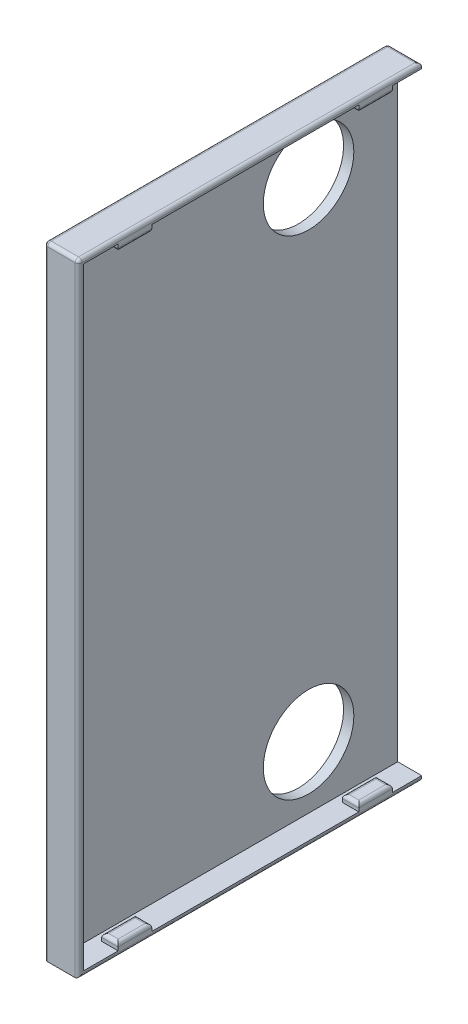
SolidWorks part; units mm, degrees
ref_plane "Plano frontal" through (0, 0, 0) normal (1, 0, 0) x (0, 1, 0)
ref_plane "Plano superior" through (0, 0, 0) normal (0, 0, 1) x (0, 1, 0)
ref_plane "Plano direito" through (0, 0, 0) normal (0, 1, 0) x (-1, 0, 0)
sketch "Esboço1" plane through (0, 0, 0) normal (1, 0, 0) x (0, 1, 0)
  line L1 (90.8, -51.55) -> (-90.8, -51.55)
  line L2 (90.8, -51.55) -> (90.8, 51.55)
  line L3 (90.8, 51.55) -> (-90.8, 51.55)
  line L4 (-90.8, -51.55) -> (-90.8, 51.55)
  line L5 (90.8, -51.55) -> (-90.8, 51.55) construction
  line L6 (90.8, 51.55) -> (-90.8, -51.55) construction
  point P0 (0, 0)
  dimension "D1" = 181.6
  dimension "D2" = 103.1
extrude "Ressalto-extrusão1" add sketch "Esboço1" along normal blind 10
sketch "Esboço2" plane through (10, 0, 0) normal (1, 0, 0) x (0, 1, 0)
  line L1 (89.3, -50.05) -> (-89.3, -50.05)
  line L2 (89.3, -50.05) -> (89.3, 50.05)
  line L3 (89.3, 50.05) -> (-89.3, 50.05)
  line L4 (-89.3, -50.05) -> (-89.3, 50.05)
  line L5 (89.3, -50.05) -> (-89.3, 50.05) construction
  line L6 (89.3, 50.05) -> (-89.3, -50.05) construction
  point P0 (0, 0)
  dimension "D1" = 178.6
  dimension "D2" = 100.1
extrude "Corte-extrusão1" cut sketch "Esboço2" against normal blind 7
sketch "Esboço4" plane through (0, -89.3, 0) normal (0, 1, 0) x (-1, 0, 0)
  line L0 (-10, 50.05) -> (-10, -50.05) construction
  line L1 (-10, 40) -> (-5.2, 40)
  line L2 (-10, 40) -> (-10, 30.2)
  line L3 (-10, 30.2) -> (-5.2, 30.2)
  line L4 (-5.2, 40) -> (-5.2, 30.2)
  line L5 (-3, 50.05) -> (-10, 50.05) construction
  dimension "D1" = 9.8
  dimension "D2" = 4.8
  dimension "D3" = 10.05
extrude "Ressalto-extrusão2" add sketch "Esboço4" along normal blind 2 contours L1 L4 L3 L2
mirror "Espelhar1" about plane through (0, 0, 0) normal (0, 0, 1) of "Ressalto-extrusão2"
mirror "Espelhar2" about plane through (0, 0, 0) normal (0, 1, 0) of "Espelhar1", "Ressalto-extrusão2"
sketch "Esboço5" plane through (0, 0, -51.55) normal (0, 0, -1) x (1, 0, 0)
  line L1 (0, 90.8) -> (10, 90.8)
  line L2 (0, 90.8) -> (0, -90.8)
  line L3 (0, -90.8) -> (10, -90.8)
  line L4 (10, 90.8) -> (10, -90.8)
extrude "Corte-extrusão2" cut sketch "Esboço5" against normal blind 3
fillet "Filete3" radius 1 10 edges at (5, -90.8, -48.55) (5, 90.8, -48.55) (10, 90.8, 1.5) (10, -90.8, 1.5) (10, 0, 51.55) (0, -90.8, 1.5) (0, 0, -48.55) (0, 90.8, 1.5) (0, 0, 51.55) (5, 90.8, 51.55)
fillet "Filete6" radius 1 4 edges at (7.6, -87.3, 40) (5.2, -87.3, 35.1) (7.6, -87.3, 30.2) (10, -87.3, 35.1)
fillet "Filete7" radius 1 4 edges at (7.6, -87.3, -30.2) (5.2, -87.3, -35.1) (7.6, -87.3, -40) (10, -87.3, -35.1)
fillet "Filete8" radius 1 8 edges at (7.6, 87.3, -40) (5.2, 87.3, -35.1) (7.6, 87.3, -30.2) (10, 87.3, -35.1) (7.6, 87.3, 30.2) (5.2, 87.3, 35.1) (7.6, 87.3, 40) (10, 87.3, 35.1)
sketch "Esboço6" plane through (0, 0, 0) normal (-1, 0, 0) x (0, -1, 0)
  line L0 (-89.8, -47.55) -> (89.8, -47.55) construction
  circle A0 centre (-71.25, -22.55) radius 13.2
  point P5 (-150.7291, 69.687)
  dimension "D3" = 26.4
  dimension "D1" = 71.25
  dimension "D2" = 25
extrude "Corte-extrusão3" cut sketch "Esboço6" against normal blind 10
mirror "Espelhar3" about plane through (0, 0, 0) normal (0, 1, 0) of "Corte-extrusão3"
